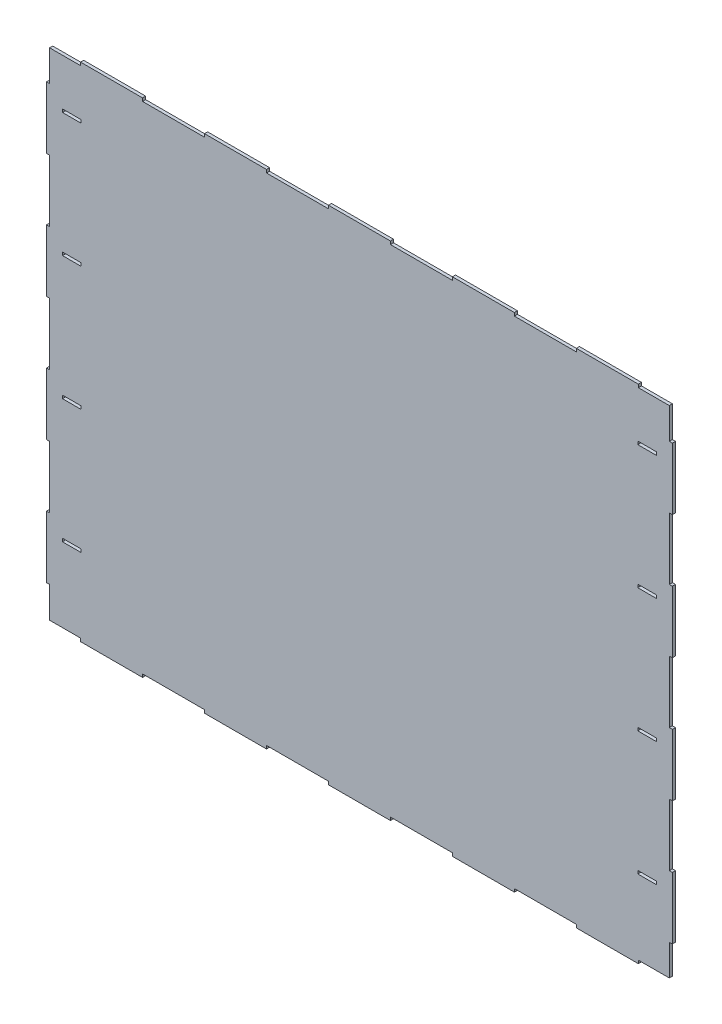
SolidWorks part; units mm, degrees
ref_plane "Front Plane" through (0, 0, 0) normal (0, 0, 1) x (1, 0, 0)
ref_plane "Top Plane" through (0, 0, 0) normal (0, 1, 0) x (1, 0, 0)
ref_plane "Right Plane" through (0, 0, 0) normal (1, 0, 0) x (0, 0, -1)
sketch "Sketch1" plane through (0, 0, 0) normal (0, 0, 1) x (1, 0, 0)
  line L0 (86.5204, 37.1469) -> (86.5204, 39.6469)
  line L1 (36.5204, 37.1469) -> (86.5204, 37.1469)
  line L2 (-38.4796, 37.1469) -> (-38.4796, 12.1469)
  line L3 (-38.4796, -362.8531) -> (-13.4796, -362.8531)
  line L4 (461.5204, 37.1469) -> (461.5204, 12.1469)
  line L5 (86.5204, 39.6469) -> (136.5204, 39.6469)
  line L6 (-13.4796, 37.1469) -> (-13.4796, 39.6469)
  line L7 (-13.4796, 39.6469) -> (36.5204, 39.6469)
  line L8 (36.5204, 37.1469) -> (36.5204, 39.6469)
  line L9 (136.5204, 37.1469) -> (136.5204, 39.6469)
  line L10 (186.5204, 37.1469) -> (186.5204, 39.6469)
  line L11 (186.5204, 39.6469) -> (236.5204, 39.6469)
  line L12 (236.5204, 37.1469) -> (236.5204, 39.6469)
  line L13 (286.5204, 37.1469) -> (286.5204, 39.6469)
  line L14 (286.5204, 39.6469) -> (336.5204, 39.6469)
  line L15 (336.5204, 37.1469) -> (336.5204, 39.6469)
  line L16 (386.5204, 37.1469) -> (386.5204, 39.6469)
  line L17 (386.5204, 39.6469) -> (436.5204, 39.6469)
  line L18 (436.5204, 37.1469) -> (436.5204, 39.6469)
  line L19 (-13.4796, 37.1469) -> (-38.4796, 37.1469)
  line L20 (-38.4796, -162.8531) -> (461.5204, -162.8531) construction
  line L21 (436.5204, -362.8531) -> (436.5204, -365.3531)
  line L22 (136.5204, 37.1469) -> (186.5204, 37.1469)
  line L23 (236.5204, 37.1469) -> (286.5204, 37.1469)
  line L24 (336.5204, 37.1469) -> (386.5204, 37.1469)
  line L25 (436.5204, 37.1469) -> (461.5204, 37.1469)
  line L26 (486.5204, 39.6469) -> (536.5204, 39.6469) [skipped]
  line L27 (536.5204, 37.1469) -> (536.5204, 39.6469) [skipped]
  line L28 (486.5204, 37.1469) -> (486.5204, 39.6469) [skipped]
  line L29 (386.5204, -365.3531) -> (436.5204, -365.3531)
  line L30 (386.5204, -362.8531) -> (386.5204, -365.3531)
  line L31 (336.5204, -362.8531) -> (336.5204, -365.3531)
  line L32 (286.5204, -365.3531) -> (336.5204, -365.3531)
  line L33 (286.5204, -362.8531) -> (286.5204, -365.3531)
  line L34 (236.5204, -362.8531) -> (236.5204, -365.3531)
  line L35 (186.5204, -365.3531) -> (236.5204, -365.3531)
  line L36 (186.5204, -362.8531) -> (186.5204, -365.3531)
  line L37 (136.5204, -362.8531) -> (136.5204, -365.3531)
  line L38 (86.5204, -365.3531) -> (136.5204, -365.3531)
  line L39 (86.5204, -362.8531) -> (86.5204, -365.3531)
  line L40 (36.5204, -362.8531) -> (36.5204, -365.3531)
  line L41 (-13.4796, -365.3531) -> (36.5204, -365.3531)
  line L42 (-13.4796, -362.8531) -> (-13.4796, -365.3531)
  line L43 (36.5204, -362.8531) -> (86.5204, -362.8531)
  line L44 (136.5204, -362.8531) -> (186.5204, -362.8531)
  line L45 (236.5204, -362.8531) -> (286.5204, -362.8531)
  line L46 (336.5204, -362.8531) -> (386.5204, -362.8531)
  line L47 (436.5204, -362.8531) -> (461.5204, -362.8531)
  line L48 (461.5204, -37.8531) -> (461.5204, -87.8531)
  line L49 (461.5204, 12.1469) -> (464.0204, 12.1469)
  line L50 (461.5204, -87.8531) -> (464.0204, -87.8531)
  line L51 (461.5204, -37.8531) -> (464.0204, -37.8531)
  line L52 (464.0204, 12.1469) -> (464.0204, -37.8531)
  line L53 (464.0204, -87.8531) -> (464.0204, -137.8531)
  line L54 (461.5204, -137.8531) -> (464.0204, -137.8531)
  line L55 (461.5204, -187.8531) -> (464.0204, -187.8531)
  line L56 (464.0204, -187.8531) -> (464.0204, -237.8531)
  line L57 (461.5204, -237.8531) -> (464.0204, -237.8531)
  line L58 (461.5204, -287.8531) -> (464.0204, -287.8531)
  line L59 (464.0204, -287.8531) -> (464.0204, -337.8531)
  line L60 (461.5204, -337.8531) -> (464.0204, -337.8531)
  line L61 (461.5204, -137.8531) -> (461.5204, -187.8531)
  line L62 (461.5204, -237.8531) -> (461.5204, -287.8531)
  line L63 (461.5204, -337.8531) -> (461.5204, -362.8531)
  line L64 (211.5204, -162.8531) -> (211.5204, -619.2144) construction
  line L65 (-38.4796, -337.8531) -> (-40.9796, -337.8531)
  line L66 (-40.9796, -287.8531) -> (-40.9796, -337.8531)
  line L67 (-38.4796, -237.8531) -> (-40.9796, -237.8531)
  line L68 (-38.4796, -287.8531) -> (-40.9796, -287.8531)
  line L69 (-40.9796, -187.8531) -> (-40.9796, -237.8531)
  line L70 (-38.4796, -187.8531) -> (-40.9796, -187.8531)
  line L71 (-38.4796, -137.8531) -> (-40.9796, -137.8531)
  line L72 (-40.9796, -87.8531) -> (-40.9796, -137.8531)
  line L73 (-38.4796, -87.8531) -> (-40.9796, -87.8531)
  line L74 (-38.4796, -37.8531) -> (-40.9796, -37.8531)
  line L75 (-40.9796, 12.1469) -> (-40.9796, -37.8531)
  line L76 (-38.4796, 12.1469) -> (-40.9796, 12.1469)
  line L77 (-38.4796, -37.8531) -> (-38.4796, -87.8531)
  line L78 (-38.4796, -137.8531) -> (-38.4796, -187.8531)
  line L79 (-38.4796, -237.8531) -> (-38.4796, -287.8531)
  line L80 (-38.4796, -337.8531) -> (-38.4796, -362.8531)
  line L81 (436.1135, -100.3531) -> (451.1135, -100.3531)
  line L82 (436.1135, -0.3531) -> (451.1135, -0.3531)
  line L83 (436.1135, -0.3531) -> (436.1135, -2.8531)
  line L84 (436.1135, -2.8531) -> (451.1135, -2.8531)
  line L85 (451.1135, -0.3531) -> (451.1135, -2.8531)
  line L86 (436.1135, -102.8531) -> (451.1135, -102.8531)
  line L87 (451.1135, -100.3531) -> (451.1135, -102.8531)
  line L88 (436.1135, -100.3531) -> (436.1135, -102.8531)
  line L89 (436.1135, -200.3531) -> (451.1135, -200.3531)
  line L90 (436.1135, -202.8531) -> (451.1135, -202.8531)
  line L91 (451.1135, -200.3531) -> (451.1135, -202.8531)
  line L92 (436.1135, -200.3531) -> (436.1135, -202.8531)
  line L93 (436.1135, -300.3531) -> (451.1135, -300.3531)
  line L94 (436.1135, -302.8531) -> (451.1135, -302.8531)
  line L95 (451.1135, -300.3531) -> (451.1135, -302.8531)
  line L96 (436.1135, -300.3531) -> (436.1135, -302.8531)
  line L97 (-13.0727, -300.3531) -> (-13.0727, -302.8531)
  line L98 (-28.0727, -300.3531) -> (-28.0727, -302.8531)
  line L99 (-13.0727, -302.8531) -> (-28.0727, -302.8531)
  line L100 (-13.0727, -300.3531) -> (-28.0727, -300.3531)
  line L101 (436.1135, -400.3531) -> (451.1135, -400.3531) [skipped]
  line L102 (436.1135, -402.8531) -> (451.1135, -402.8531) [skipped]
  line L103 (451.1135, -400.3531) -> (451.1135, -402.8531) [skipped]
  line L104 (436.1135, -400.3531) -> (436.1135, -402.8531) [skipped]
  line L105 (-13.0727, -200.3531) -> (-13.0727, -202.8531)
  line L106 (-28.0727, -200.3531) -> (-28.0727, -202.8531)
  line L107 (-13.0727, -202.8531) -> (-28.0727, -202.8531)
  line L108 (-13.0727, -200.3531) -> (-28.0727, -200.3531)
  line L109 (-13.0727, -100.3531) -> (-13.0727, -102.8531)
  line L110 (-28.0727, -100.3531) -> (-28.0727, -102.8531)
  line L111 (-13.0727, -102.8531) -> (-28.0727, -102.8531)
  line L112 (-13.0727, -100.3531) -> (-28.0727, -100.3531)
  line L113 (-28.0727, -0.3531) -> (-28.0727, -2.8531)
  line L114 (-13.0727, -2.8531) -> (-28.0727, -2.8531)
  line L115 (-13.0727, -0.3531) -> (-13.0727, -2.8531)
  line L116 (-13.0727, -0.3531) -> (-28.0727, -0.3531)
  dimension "D1" = 500
  dimension "D2" = 400
  dimension "D3" = 50
  dimension "D4" = 2.5
  dimension "D6" = 25
  dimension "D7" = 50
  dimension "D8" = 25
  dimension "D10" = 2.5
  dimension "D11" = 5
  dimension "D5" = 6
  dimension "D9" = 4
extrude "50X40 top plane" add sketch "Sketch1" along normal blind 2.5
